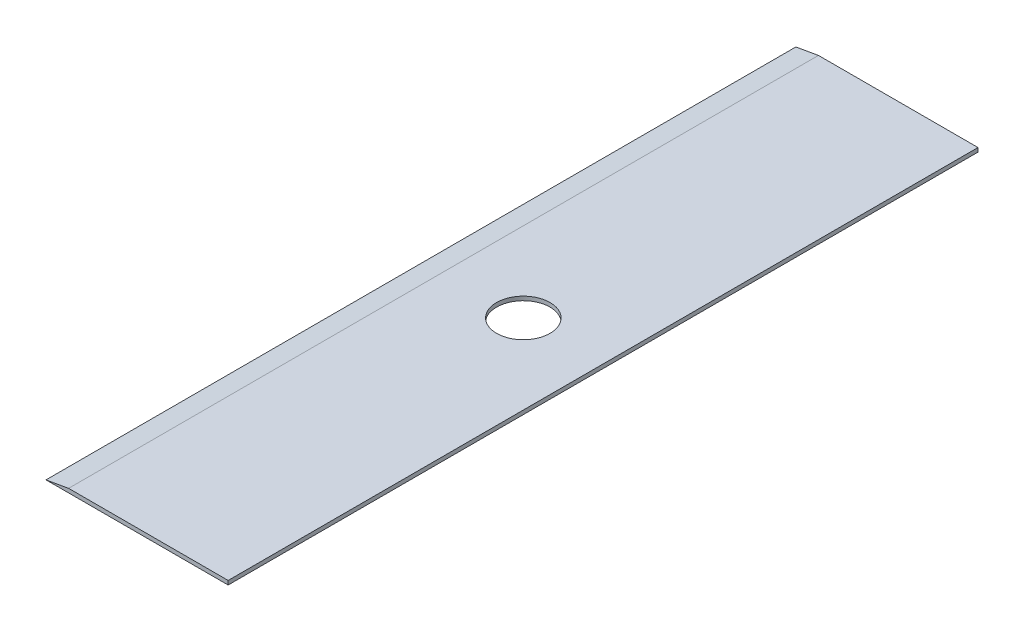
SolidWorks part; units mm, degrees
material "1023 Carbon Steel Sheet (SS)"
ref_plane "Front Plane" through (0, 0, 0) normal (0, 0, 1) x (1, 0, 0)
ref_plane "Top Plane" through (0, 0, 0) normal (0, 1, 0) x (1, 0, 0)
ref_plane "Right Plane" through (0, 0, 0) normal (1, 0, 0) x (0, 0, -1)
sketch "Sketch2" plane through (0, 0, 0) normal (0, 0, 1) x (1, 0, 0)
  line L0 (0, 0) -> (5.08, 0)
  line L1 (5.08, 0) -> (5.08, 0.127)
  line L2 (5.08, 0.127) -> (0, 0.127)
  line L3 (0, 0) -> (-0.7203, 0)
  line L4 (-0.7203, 0) -> (0, 0.127)
  dimension "D1" = 5.08
  dimension "D2" = 0.127
  dimension "D3" = 10
extrude "Boss-Extrude1" add sketch "Sketch2" along normal mid plane 23.876
sketch "Sketch3" plane through (0, 0.127, 0) normal (0, 1, 0) x (1, 0, 0)
  line L0 (5.08, -11.938) -> (5.08, 11.938) construction
  line L1 (5.08, 11.938) -> (0, 11.938) construction
  circle A0 centre (2.54, 0) radius 0.8509
  point P4 (5.08, 0)
  point P7 (2.54, 11.938)
  dimension "D1" = 1.7018
extrude "Cut-Extrude1" cut sketch "Sketch3" against normal up to surface (0.127 mm away) up to face at (2.1799, 0, 0)
